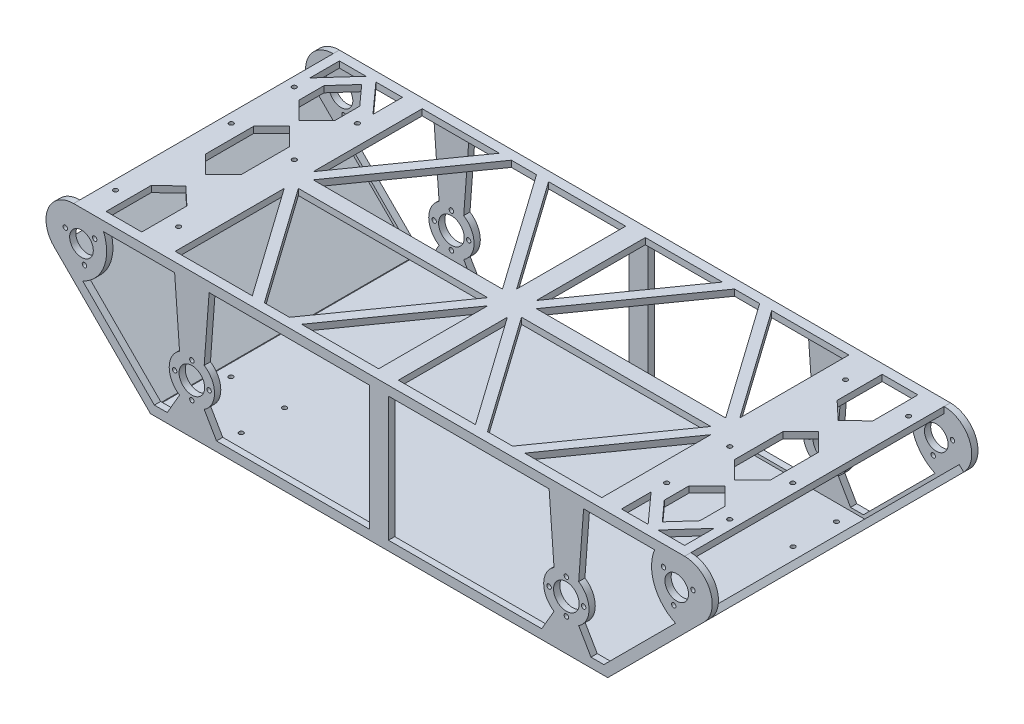
SolidWorks part; units mm, degrees
material "6061-T6 (SS)"
ref_plane "Alzado" through (0, 0, 0) normal (0, 0, 1) x (1, 0, 0)
ref_plane "Planta" through (0, 0, 0) normal (0, 1, 0) x (1, 0, 0)
ref_plane "Vista lateral" through (0, 0, 0) normal (1, 0, 0) x (0, 0, -1)
sketch "Sketch1" plane through (0, 0, 0) normal (0, 1, 0) x (1, 0, 0)
  line L1 (-229.3786, -128.5) -> (229.3787, -128.5)
  line L2 (-229.3786, -128.5) -> (-229.3786, 128.5)
  line L3 (-229.3786, 128.5) -> (229.3787, 128.5)
  line L4 (229.3787, -128.5) -> (229.3787, 128.5)
  line L5 (-229.3786, -128.5) -> (229.3787, 128.5) construction
  line L6 (-229.3786, 128.5) -> (229.3787, -128.5) construction
  point P0 (0, 0)
  dimension "D1" = 257
  dimension "D2" = 458.7573
extrude "Boss-Extrude1" add sketch "Sketch1" against normal blind 6.35
sketch "Sketch2" plane through (0, 0, 128.5) normal (0, 0, 1) x (1, 0, 0)
  line L0 (-229.3786, 0) -> (-325.3344, 95.9558) construction
  line L3 (229.3787, 0) -> (-229.3786, 0) construction
  line L4 (-309.9902, 133) -> (309.9902, 133) construction
  line L5 (325.3344, 95.9558) -> (229.3787, 0) construction
  line L6 (-229.3786, 0) -> (-229.3786, 133) construction
  line L7 (329.8246, 91.4657) -> (232.0089, -6.35)
  line L8 (232.0089, -6.35) -> (-232.0089, -6.35)
  line L9 (-232.0089, -6.35) -> (-329.8246, 91.4657)
  line L10 (-309.9902, 139.35) -> (309.9902, 139.35)
  arc A0 (-325.3344, 95.9558) -> (-309.9902, 133) centre (-309.9902, 111.3) cw construction
  arc A1 (309.9902, 133) -> (325.3344, 95.9558) centre (309.9902, 111.3) cw construction
  arc A2 (-329.8246, 91.4657) -> (-309.9902, 139.35) centre (-309.9902, 111.3) cw
  arc A3 (309.9902, 139.35) -> (329.8246, 91.4657) centre (309.9902, 111.3) cw
  point P11 (0, 133)
  dimension "D2" = 21.7
  dimension "D3" = 45
  dimension "D1" = 133
  dimension "D4" = 6.35
extrude "Boss-Extrude2" add sketch "Sketch2" along normal blind 6.35
mirror "Mirror1" about plane through (0, 0, 0) normal (0, 0, 1) of "Boss-Extrude2"
sketch "Sketch3" plane through (0, 139.35, 0) normal (0, 1, 0) x (1, 0, 0)
  line L1 (-309.9902, -128.5) -> (309.9902, -128.5)
  line L2 (-309.9902, -128.5) -> (-309.9902, 128.5)
  line L3 (-309.9902, 128.5) -> (309.9902, 128.5)
  line L4 (309.9902, -128.5) -> (309.9902, 128.5)
  line L5 (-309.9902, -128.5) -> (309.9902, 128.5) construction
  line L6 (-309.9902, 128.5) -> (309.9902, -128.5) construction
  point P0 (0, 0)
extrude "Boss-Extrude3" add sketch "Sketch3" against normal blind 6.35
sketch "Sketch5" plane through (119.1795, -119.1795, 0) normal (0.7071, -0.7071, 0) x (0, 0, -1)
  line L1 (-134.85, 297.8972) -> (134.85, 297.8972)
  line L2 (-134.85, 297.8972) -> (-134.85, 162.6952)
  line L3 (-134.85, 162.6952) -> (134.85, 162.6952)
  line L4 (134.85, 297.8972) -> (134.85, 162.6952)
  line L6 (134.85, 159.5649) -> (134.85, 297.8972) construction
  line L7 (-128.5, 162.1952) -> (128.5, 162.1952) construction
  dimension "D1" = 0.5
extrude "Boss-Extrude4" add sketch "Sketch5" against normal blind 6.35
mirror "Mirror5" about plane through (0, 0, 0) normal (1, 0, 0) of "Boss-Extrude4"
sketch "Sketch6" plane through (0, 0, 134.85) normal (0, 0, 1) x (1, 0, 0)
  line L0 (0, -1.5) -> (0, 134.5) construction
  line L1 (229.7929, -1.5) -> (-229.7929, -1.5) construction
  line L2 (-310, 134.5) -> (310, 134.5) construction
  circle A0 centre (-302.0233, 108) radius 12
  circle A1 centre (-190, 44) radius 13
  circle A4 centre (-190, 44) radius 13 construction
  circle A5 centre (-318.468, 113.9854) radius 2.25
  circle A6 centre (-288.6176, 119.2488) radius 2.25
  circle A7 centre (-298.9845, 90.7659) radius 2.25
  circle A8 centre (-190, 61.5) radius 2.25
  circle A9 centre (-172.5, 44) radius 2.25
  circle A10 centre (-190, 44) radius 13
  circle A11 centre (-190, 26.5) radius 2.25
  circle A12 centre (-190, 44) radius 13
  circle A13 centre (-207.5, 44) radius 2.25
  circle A14 centre (-190, 44) radius 13
  circle A15 centre (190, 44) radius 13
  circle A16 centre (207.5, 44) radius 2.25
  circle A17 centre (190, 44) radius 13
  circle A18 centre (190, 26.5) radius 2.25
  circle A19 centre (190, 44) radius 13
  circle A20 centre (172.5, 44) radius 2.25
  circle A21 centre (190, 61.5) radius 2.25
  circle A22 centre (298.9845, 90.7659) radius 2.25
  circle A23 centre (288.6176, 119.2488) radius 2.25
  circle A24 centre (318.468, 113.9854) radius 2.25
  circle A25 centre (190, 44) radius 13
  circle A26 centre (302.0233, 108) radius 12
  circle A27 centre (-302.0233, 108) radius 31
  point P23 (-302.0233, 108)
  point P37 (-190, 44)
  point P58 (190, 44)
  point P59 (302.0233, 108)
  dimension "D1" = 24
  dimension "D2" = 3
  dimension "D3" = 4.5
  dimension "D4" = 4
  dimension "D5" = 4.5
  dimension "D6" = 62
extrude "Cut-Extrude1" cut sketch "Sketch6" against normal through all both and the other way through all contours A0 | A1 | A15 | A26 | A5 | A7 | A6 | A8 | A13 | A11 | A9 | A18 | A16 | A21 | A20 | A24 | A23 | A22
sketch "Sketch7" plane through (0, -6.35, 0) normal (0, -1, 0) x (1, 0, 0)
  circle A0 centre (-217.25, 112) radius 2.25
  circle A1 centre (-162.75, 112) radius 2.25
  circle A2 centre (-162.75, 68) radius 2.25
  circle A3 centre (-217.25, 68) radius 2.25
  circle A4 centre (217.25, -112) radius 2.25
  circle A5 centre (217.25, -68) radius 2.25
  circle A6 centre (162.75, -68) radius 2.25
  circle A7 centre (162.75, -112) radius 2.25
  dimension "D1" = 4.5
extrude "Cut-Extrude2" cut sketch "Sketch7" against normal blind 10
sketch "Sketch8" plane through (0, 139.35, 0) normal (0, 1, 0) x (1, 0, 0)
  circle A0 centre (300.438, -15.52) radius 2.25
  circle A1 centre (236.438, -15.52) radius 2.25
  circle A2 centre (236.438, -79.52) radius 2.25
  circle A3 centre (300.438, -79.52) radius 2.25
  circle A4 centre (-300.438, 79.52) radius 2.25
  circle A5 centre (-236.438, 79.52) radius 2.25
  circle A6 centre (-236.438, 15.52) radius 2.25
  circle A7 centre (-300.438, 15.52) radius 2.25
  circle A8 centre (-300.438, -101.93) radius 2.25
  circle A9 centre (-236.438, -101.93) radius 2.25
  circle A10 centre (236.438, 101.93) radius 2.25
  circle A11 centre (300.438, 101.93) radius 2.25
  dimension "D1" = 4.5
  dimension "D2" = 4.5
extrude "Cut-Extrude3" cut sketch "Sketch8" against normal blind 10
sketch "Sketch9" plane through (0, 0, 134.85) normal (0, 0, 1) x (1, 0, 0)
  line L0 (0, -6.35) -> (0, 139.35) construction
  line L1 (-232.0089, -6.35) -> (232.0089, -6.35) construction
  line L2 (309.9902, 139.35) -> (-309.9902, 139.35) construction
  line L3 (0, 139.35) -> (0, -6.35) construction
  line L4 (-9.525, 129.825) -> (-172.5, 129.825)
  line L5 (-300.7801, 75.8915) -> (-228.0635, 3.175)
  line L6 (-228.0635, 3.175) -> (-215, 3.175)
  line L7 (-329.8246, 91.4657) -> (-232.0089, -6.35)
  line L8 (-232.0089, -6.35) -> (232.0089, -6.35)
  line L9 (232.0089, -6.35) -> (329.8246, 91.4657)
  line L10 (309.9902, 139.35) -> (-309.9902, 139.35)
  line L11 (-329.8246, 91.4657) -> (-232.0089, -6.35) construction
  line L12 (-232.0089, -6.35) -> (0, -6.35) construction
  line L14 (0, 139.35) -> (-309.9902, 139.35) construction
  line L15 (-9.525, 129.825) -> (-9.525, 3.175)
  line L16 (-190, -6.35) -> (-190, 139.35) construction
  line L17 (-215, 3.175) -> (-202.5, 24.6933)
  line L18 (-165, 3.175) -> (-177.5, 24.6933)
  line L19 (-165, 3.175) -> (-9.525, 3.175)
  line L20 (-228.0635, 3.175) -> (-9.525, 3.175) construction
  line L21 (-91.0125, 3.175) -> (-9.525, 129.825) construction
  line L22 (-202.5, 63.3067) -> (-207.5, 129.825)
  line L23 (-172.5, 129.825) -> (-177.5, 63.3067)
  line L24 (-207.5, 129.825) -> (-279.5693, 129.825)
  line L25 (-9.525, 129.825) -> (-309.9902, 129.825) construction
  line L26 (-172.5, 129.825) -> (-91.0125, 3.175) construction
  line L27 (-323.0894, 98.2008) -> (-228.0635, 3.175) construction
  line L28 (207.5, 129.825) -> (279.5693, 129.825)
  line L29 (202.5, 63.3067) -> (207.5, 129.825)
  line L30 (215, 3.175) -> (202.5, 24.6933)
  line L31 (228.0635, 3.175) -> (215, 3.175)
  line L32 (300.7801, 75.8915) -> (228.0635, 3.175)
  line L33 (165, 3.175) -> (9.525, 3.175)
  line L34 (9.525, 129.825) -> (9.525, 3.175)
  line L35 (9.525, 129.825) -> (172.5, 129.825)
  line L36 (172.5, 129.825) -> (177.5, 63.3067)
  line L37 (165, 3.175) -> (177.5, 24.6933)
  arc A3 (-279.5693, 129.825) -> (-300.7801, 75.8915) centre (-318.468, 113.9854) cw
  arc A4 (-309.9902, 139.35) -> (-329.8246, 91.4657) centre (-309.9902, 111.3) ccw
  arc A5 (329.8246, 91.4657) -> (309.9902, 139.35) centre (309.9902, 111.3) ccw
  arc A6 (-309.9902, 139.35) -> (-329.8246, 91.4657) centre (-309.9902, 111.3) ccw construction
  circle A8 centre (-318.468, 113.9854) radius 2.25 construction
  arc A9 (-177.5, 24.6933) -> (-177.5, 63.3067) centre (-190, 44) ccw
  circle A10 centre (-190, 44) radius 13 construction
  arc A11 (-202.5, 63.3067) -> (-202.5, 24.6933) centre (-190, 44) ccw
  arc A12 (-309.9902, 129.825) -> (-323.0894, 98.2008) centre (-309.9902, 111.3) ccw construction
  arc A13 (279.5693, 129.825) -> (300.7801, 75.8915) centre (318.468, 113.9854) ccw
  arc A14 (202.5, 63.3067) -> (202.5, 24.6933) centre (190, 44) cw
  arc A15 (177.5, 24.6933) -> (177.5, 63.3067) centre (190, 44) cw
  dimension "D1" = 0
  dimension "D3" = 42
  dimension "D4" = 50
  dimension "D5" = 10
  dimension "D2" = 9.525
  dimension "D6" = 25
  dimension "D7" = 35
extrude "Cut-Extrude4" cut sketch "Sketch9" against normal through all
sketch "Sketch10" plane through (0, 139.35, 0) normal (0, 1, 0) x (1, 0, 0)
  line L0 (0, 134.85) -> (0, -134.85) construction
  line L1 (309.9902, -134.85) -> (-309.9902, -134.85) construction
  line L2 (-300.4652, 125.325) -> (-300.4652, 95.325)
  line L3 (-300.4652, 95.325) -> (-273.4516, 125.325)
  line L4 (-273.4516, 125.325) -> (-300.4652, 125.325)
  line L5 (-263.4516, 125.325) -> (-236.438, 125.325)
  line L6 (-236.438, 125.325) -> (-236.438, 95.325)
  line L7 (-236.438, 95.325) -> (-263.4516, 125.325)
  line L8 (-309.9902, 128.5) -> (-309.9902, -128.5) construction
  line L9 (309.9902, 134.85) -> (-309.9902, 134.85) construction
  line L10 (-236.438, 134.85) -> (-236.438, 79.52) construction
  line L11 (-286.5358, 95.85) -> (-268.4516, 115.9334)
  line L12 (-281.2713, 95.85) -> (-255.6046, 95.85) construction
  line L13 (-268.4516, 115.9334) -> (-250.3674, 95.85)
  line L15 (-286.5358, 95.85) -> (-286.5358, 70.6042)
  line L16 (-286.5358, 70.6042) -> (-268.4516, 52.52)
  line L17 (-268.4516, 52.52) -> (-250.3674, 70.6042)
  line L18 (-250.3674, 70.6042) -> (-250.3674, 95.85)
  line L19 (-236.438, 47.52) -> (-300.438, 47.52) construction
  line L20 (-300.438, 79.52) -> (-236.438, 79.52) construction
  line L21 (-300.438, 79.52) -> (-300.438, 15.52) construction
  line L22 (-300.438, 15.52) -> (-236.438, 15.52) construction
  line L23 (-236.438, 79.52) -> (-236.438, 15.52) construction
  line L31 (-286.5358, -24.4358) -> (-286.5358, 24.4358)
  line L32 (-286.5358, 24.4358) -> (-268.4516, 42.52)
  line L33 (-268.4516, 42.52) -> (-250.3674, 24.4358)
  line L34 (-250.3674, 24.4358) -> (-250.3674, -24.4358)
  line L36 (309.9902, 0) -> (286.5358, 0) construction
  line L37 (-216.438, 125.325) -> (-216.438, 14.6746)
  line L38 (-216.438, 14.6746) -> (-138.219, 125.325)
  line L39 (-216.438, 125.325) -> (-138.219, 125.325)
  line L40 (-88.219, 125.325) -> (-10, 125.325)
  line L41 (-10, 125.325) -> (-10, 14.6746)
  line L42 (-10, 14.6746) -> (-88.219, 125.325)
  line L43 (-209.2634, 7.5) -> (-125.9727, 125.325)
  line L44 (-100.4652, 125.325) -> (-17.1746, 7.5)
  line L45 (-17.1746, 7.5) -> (-209.2634, 7.5)
  line L46 (-100.4652, 125.325) -> (-125.9727, 125.325)
  line L51 (-300.438, -79.52) -> (-236.438, -79.52) construction
  line L52 (-286.5358, -79.52) -> (-268.4516, -62.52)
  line L53 (-268.4516, -62.52) -> (-250.3674, -79.52)
  line L54 (-100.4652, -125.325) -> (-125.9727, -125.325)
  line L55 (-17.1746, -7.5) -> (-209.2634, -7.5)
  line L56 (-100.4652, -125.325) -> (-17.1746, -7.5)
  line L57 (-209.2634, -7.5) -> (-125.9727, -125.325)
  line L58 (-10, -14.6746) -> (-88.219, -125.325)
  line L59 (-10, -125.325) -> (-10, -14.6746)
  line L60 (-88.219, -125.325) -> (-10, -125.325)
  line L61 (-216.438, -125.325) -> (-138.219, -125.325)
  line L62 (-216.438, -14.6746) -> (-138.219, -125.325)
  line L63 (-216.438, -125.325) -> (-216.438, -14.6746)
  line L64 (-268.4516, -42.52) -> (-250.3674, -24.4358)
  line L65 (-286.5358, -24.4358) -> (-268.4516, -42.52)
  line L78 (-250.3674, -79.52) -> (-250.3674, -125.325)
  line L79 (-250.3674, -125.325) -> (-286.5358, -125.325)
  line L88 (-286.5358, -125.325) -> (-286.5358, -79.52)
  line L89 (216.438, -125.325) -> (216.438, -14.6746)
  line L114 (0, 24.6746) -> (-24.6746, 0) construction
  line L141 (-286.5358, 0) -> (-309.9902, 0) construction
  line L142 (250.3674, 0) -> (-250.3674, 0) construction
  line L143 (-201.7634, 0) -> (-236.438, 34.6746) construction
  line L144 (216.438, -14.6746) -> (138.219, -125.325)
  line L145 (216.438, -125.325) -> (138.219, -125.325)
  line L146 (88.219, -125.325) -> (10, -125.325)
  line L147 (10, -125.325) -> (10, -14.6746)
  line L148 (10, -14.6746) -> (88.219, -125.325)
  line L149 (209.2634, -7.5) -> (125.9727, -125.325)
  line L150 (100.4652, -125.325) -> (17.1746, -7.5)
  line L151 (17.1746, -7.5) -> (209.2634, -7.5)
  line L152 (100.4652, -125.325) -> (125.9727, -125.325)
  line L153 (100.4652, 125.325) -> (125.9727, 125.325)
  line L154 (17.1746, 7.5) -> (209.2634, 7.5)
  line L155 (100.4652, 125.325) -> (17.1746, 7.5)
  line L156 (209.2634, 7.5) -> (125.9727, 125.325)
  line L157 (10, 14.6746) -> (88.219, 125.325)
  line L158 (10, 125.325) -> (10, 14.6746)
  line L159 (88.219, 125.325) -> (10, 125.325)
  line L160 (216.438, 125.325) -> (138.219, 125.325)
  line L161 (216.438, 14.6746) -> (138.219, 125.325)
  line L162 (216.438, 125.325) -> (216.438, 14.6746)
  line L163 (286.5358, 24.4358) -> (286.5358, -24.4358)
  line L164 (286.5358, 24.4358) -> (268.4516, 42.52)
  line L165 (268.4516, 42.52) -> (250.3674, 24.4358)
  line L166 (250.3674, -24.4358) -> (250.3674, 24.4358)
  line L167 (268.4516, -42.52) -> (250.3674, -24.4358)
  line L168 (286.5358, -24.4358) -> (268.4516, -42.52)
  line L169 (300.4652, -95.325) -> (273.4516, -125.325)
  line L170 (273.4516, -125.325) -> (300.4652, -125.325)
  line L171 (300.4652, -125.325) -> (300.4652, -95.325)
  line L172 (236.438, -95.325) -> (263.4516, -125.325)
  line L173 (263.4516, -125.325) -> (236.438, -125.325)
  line L174 (236.438, -125.325) -> (236.438, -95.325)
  line L175 (268.4516, -115.9334) -> (250.3674, -95.85)
  line L176 (250.3674, -70.6042) -> (250.3674, -95.85)
  line L177 (268.4516, -52.52) -> (250.3674, -70.6042)
  line L178 (286.5358, -70.6042) -> (268.4516, -52.52)
  line L179 (286.5358, -95.85) -> (286.5358, -70.6042)
  line L180 (286.5358, -95.85) -> (268.4516, -115.9334)
  line L181 (286.5358, 125.325) -> (286.5358, 79.52)
  line L182 (286.5358, 79.52) -> (268.4516, 62.52)
  line L183 (268.4516, 62.52) -> (250.3674, 79.52)
  line L184 (250.3674, 79.52) -> (250.3674, 125.325)
  line L185 (250.3674, 125.325) -> (286.5358, 125.325)
  point P6 (0, 0)
  point P32 (-300.438, 47.52)
  point P43 (0, 0)
  point P44 (0, 0)
  point P49 (268.438, 59.3835)
  point P94 (0, 0)
  point P120 (0, 0)
  dimension "D1" = 9.525
  dimension "D2" = 9.525
  dimension "D3" = 30
  dimension "D4" = 10
  dimension "D5" = 10
  dimension "D6" = 10
  dimension "D7" = 5
  dimension "D8" = 20
  dimension "D9" = 10
  dimension "D10" = 50
  dimension "D11" = 10
  dimension "D12" = 10
  dimension "D13" = 15
  dimension "D14" = 45
  dimension "D15" = 45
  dimension "D16" = 20
  dimension "D17" = 2
extrude "Cut-Extrude5" cut sketch "Sketch10" against normal up to surface (6.35 mm away) up to face at (-298.188, 133, 101.93)
equation "\"W\"= 6.35"
equation "\"D1@Boss-Extrude1\"=\"W\""
equation "\"D4@Sketch2\"=\"W\""
